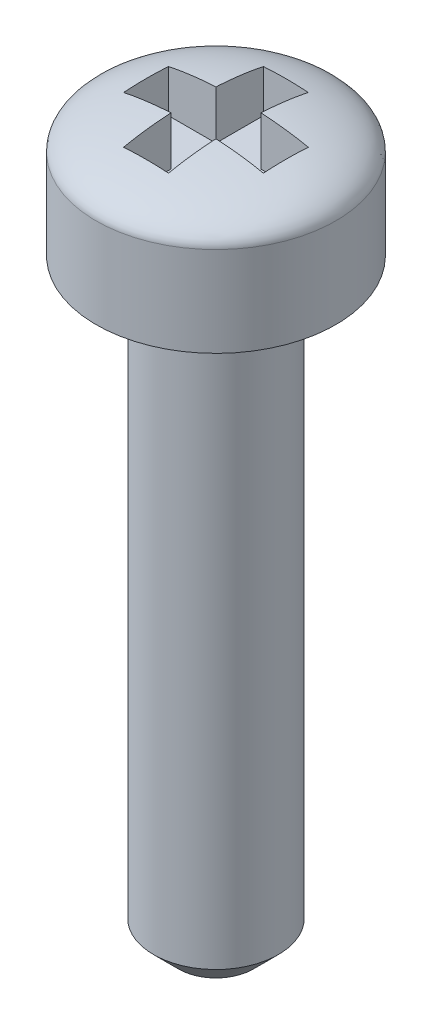
SolidWorks part; units mm, degrees
ref_plane "Front Plane" through (0, 0, 0) normal (0, 0, 1) x (1, 0, 0)
ref_plane "Top Plane" through (0, 0, 0) normal (0, 1, 0) x (1, 0, 0)
ref_plane "Right Plane" through (0, 0, 0) normal (1, 0, 0) x (0, 0, -1)
sketch "Sketch2" plane through (0, 0, 0) normal (0, 0, 1) x (1, 0, 0)
  line L0 (-2.4, -2.5) -> (-2.4, -0.7)
  line L1 (-1.25, -2.5) -> (-2.4, -2.5)
  line L2 (0, -14.5) -> (0, 0)
  line L3 (0, -14.5) -> (-0.75, -14.5)
  line L4 (-1.25, -2.5) -> (-1.25, -14)
  line L5 (0, 0) -> (0, -14.5) construction
  line L6 (-0.75, -14.5) -> (-1.25, -14)
  ellipse E0 centre (0, -0.7) end of major axis (-2.4, -0.7) minor radius 0.7 (0, 0) -> (-2.4, -0.7) ccw
  point P1 (-1.25, -14.5)
  dimension "D1" = 1.25
  dimension "D2" = 2.4
  dimension "D3" = 2.5
  dimension "D4" = 1.8
  dimension "D5" = 12
revolve "Revolve1" add sketch "Sketch2" angle 360 about L5
sketch "Sketch3" plane through (0, 0, 0) normal (0, 1, 0) x (1, 0, 0)
  line L0 (-0.45, 1.4) -> (0.45, -1.4) construction
  line L1 (-0.45, 1.4) -> (0.45, 1.4)
  line L2 (-0.45, 1.4) -> (-0.45, 0.45)
  line L3 (-0.45, -1.4) -> (0.45, -1.4)
  line L4 (0.45, 1.4) -> (0.45, 0.45)
  line L5 (-1.4, -0.45) -> (-0.45, -0.45)
  line L6 (-1.4, -0.45) -> (-1.4, 0.45)
  line L7 (-1.4, 0.45) -> (-0.45, 0.45)
  line L8 (1.4, -0.45) -> (1.4, 0.45)
  line L9 (-1.4, -0.45) -> (1.4, 0.45) construction
  line L10 (-0.45, -0.45) -> (-0.45, -1.4)
  line L11 (0.45, 0.45) -> (1.4, 0.45)
  line L12 (0.45, -0.45) -> (0.45, -1.4)
  line L13 (0.45, -0.45) -> (1.4, -0.45)
  dimension "D1" = 2.8
  dimension "D2" = 0.9
extrude "Cut-Extrude1" cut sketch "Sketch3" against normal blind 1
